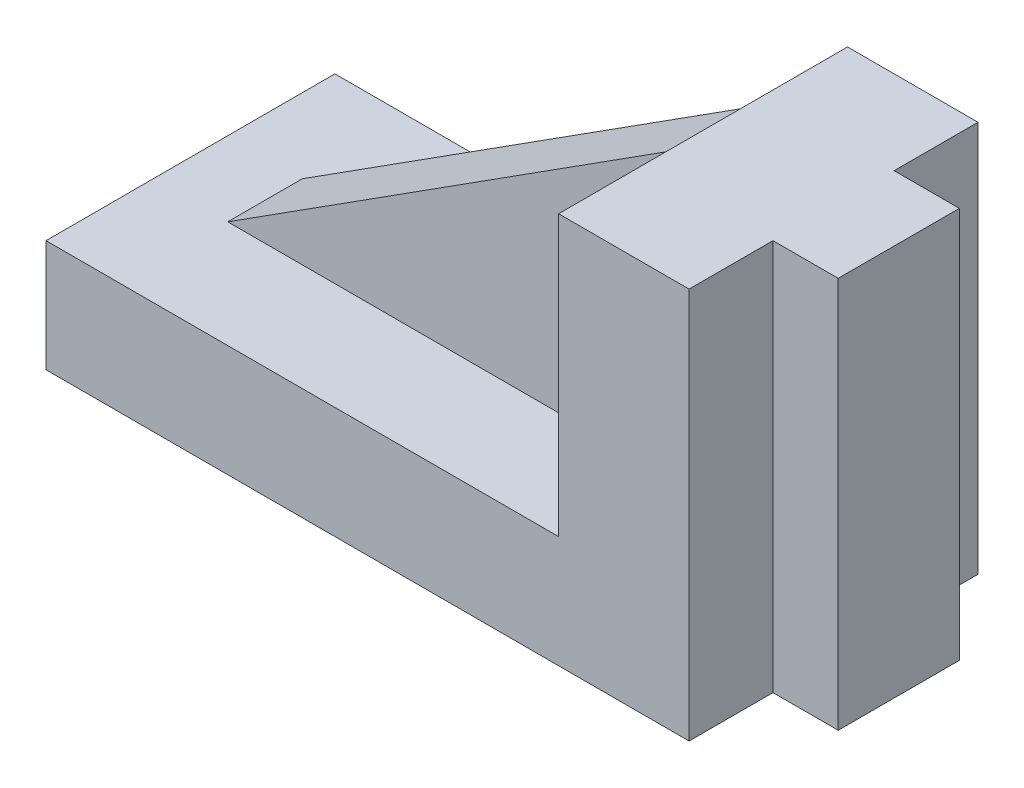
SolidWorks part; units mm, degrees
ref_plane "Front Plane" through (0, 0, 0) normal (0, 0, 1) x (1, 0, 0)
ref_plane "Top Plane" through (0, 0, 0) normal (0, 1, 0) x (1, 0, 0)
ref_plane "Right Plane" through (0, 0, 0) normal (1, 0, 0) x (0, 0, -1)
sketch "Sketch1" plane through (0, 0, 0) normal (0, 0, 1) x (1, 0, 0)
  line L1 (0, 0) -> (76, 0)
  line L2 (0, 0) -> (0, 42)
  line L3 (0, 42) -> (76, 42)
  line L4 (76, 0) -> (76, 42)
  dimension "D1" = 42
  dimension "D2" = 76
extrude "Boss-Extrude1" add sketch "Sketch1" along normal mid plane 31
sketch "Sketch2" plane through (76, 0, 0) normal (1, 0, 0) x (0, 0, -1)
  line L0 (-15.5, 42) -> (-6.5, 42)
  line L1 (-15.5, 42) -> (15.5, 42) construction
  line L2 (-6.5, 42) -> (-6.5, 0)
  line L3 (-15.5, 0) -> (15.5, 0) construction
  line L4 (-6.5, 0) -> (-15.5, 0)
  line L5 (-15.5, 0) -> (-15.5, 42)
  line L6 (15.5, 42) -> (6.5, 42)
  line L7 (6.5, 42) -> (6.5, 0)
  line L8 (6.5, 0) -> (15.5, 0)
  line L9 (15.5, 0) -> (15.5, 42)
  dimension "D1" = 9
extrude "Cut-Extrude1" cut sketch "Sketch2" against normal blind 7
sketch "Sketch3" plane through (0, 0, 15.5) normal (0, 0, 1) x (1, 0, 0)
  line L0 (55, 42) -> (55, 12)
  line L1 (69, 42) -> (0, 42) construction
  line L2 (55, 12) -> (0, 12)
  line L3 (0, 42) -> (0, 0) construction
  line L4 (0, 12) -> (0, 42)
  line L5 (0, 42) -> (55, 42)
  dimension "D1" = 12
  dimension "D2" = 14
extrude "Cut-Extrude2" cut sketch "Sketch3" against normal through all both and the other way through all
sketch "Sketch5" plane through (0, 0, 0) normal (0, 0, 1) x (1, 0, 0)
  line L0 (55, 42) -> (8, 12)
  line L1 (55, 12) -> (0, 12) construction
  line L2 (8, 12) -> (55, 12)
  line L3 (55, 12.6872) -> (55, 42)
  line L4 (55, 42) -> (55, 12) construction
  line L11 (69, 42) -> (55, 42)
  line L12 (55, 42) -> (55, 12)
  line L13 (55, 12) -> (0, 12)
  line L14 (0, 12) -> (0, 0)
  line L15 (0, 0) -> (69, 0)
  line L16 (69, 0) -> (69, 42)
  line L18 (55, 12.6872) -> (55, 12)
  dimension "D1" = 8
  dimension "D2" = 0
extrude "Boss-Extrude2" add sketch "Sketch5" along normal mid plane 8
